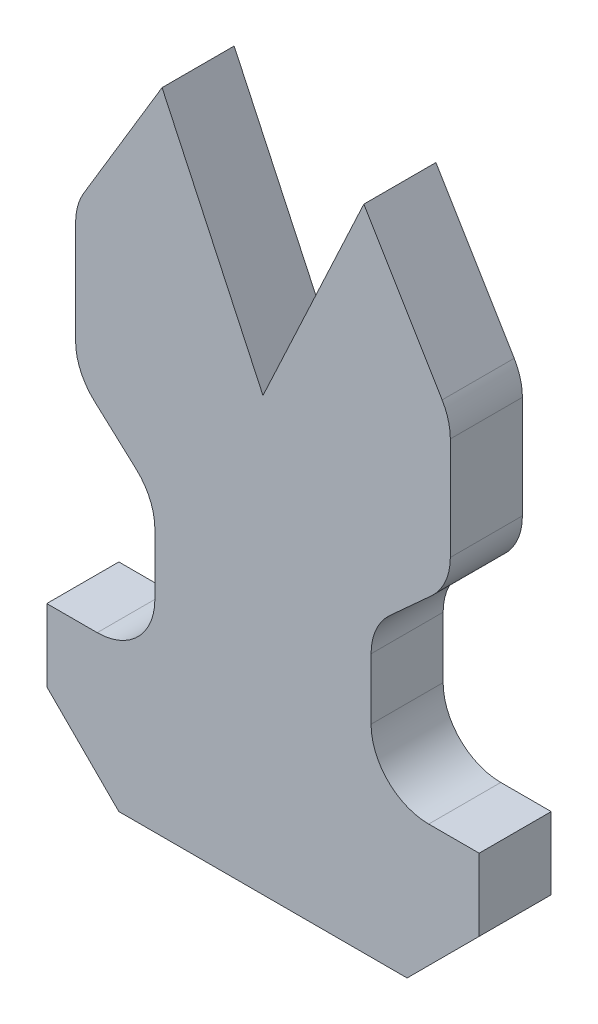
SolidWorks part; units mm, degrees
ref_plane "Piano frontale" through (0, 0, 0) normal (0, 0, 1) x (1, 0, 0)
ref_plane "Piano superiore" through (0, 0, 0) normal (0, 1, 0) x (1, 0, 0)
ref_plane "Piano destro" through (0, 0, 0) normal (1, 0, 0) x (0, 0, -1)
sketch "Schizzo1" plane through (0, 0, 0) normal (0, 0, 1) x (1, 0, 0)
  line L0 (0, 2.0281) -> (0, -3) construction
  line L1 (-1, -3) -> (1, -3)
  line L2 (1.5, -2.5) -> (1.5, -2)
  line L3 (1.5, -2) -> (1.15, -2)
  line L4 (0.75, -1.6) -> (0.75, -1.1769)
  line L5 (0.8809, -0.881) -> (1.1691, -0.619)
  line L6 (1.3, -0.3231) -> (1.3, 0.3892)
  line L7 (1.243, 0.595) -> (0.7, 1.5)
  line L8 (0.7, 1.5) -> (0, 0)
  line L9 (1, -3) -> (1.5, -2.5)
  line L10 (-1, -3) -> (-1.5, -2.5)
  line L11 (-0.7, 1.5) -> (0, 0)
  line L12 (-1.243, 0.595) -> (-0.7, 1.5)
  line L13 (-1.3, -0.3231) -> (-1.3, 0.3892)
  line L14 (-0.8809, -0.881) -> (-1.1691, -0.619)
  line L15 (-0.75, -1.6) -> (-0.75, -1.1769)
  line L16 (-1.5, -2) -> (-1.15, -2)
  line L17 (-1.5, -2.5) -> (-1.5, -2)
  arc A0 (1.15, -2) -> (0.75, -1.6) centre (1.15, -1.6) cw
  arc A1 (0.75, -1.1769) -> (0.8809, -0.881) centre (1.15, -1.1769) cw
  arc A2 (1.1691, -0.619) -> (1.3, -0.3231) centre (0.9, -0.3231) ccw
  arc A3 (1.3, 0.3892) -> (1.243, 0.595) centre (0.9, 0.3892) ccw
  arc A4 (-1.3, 0.3892) -> (-1.243, 0.595) centre (-0.9, 0.3892) cw
  arc A5 (-1.1691, -0.619) -> (-1.3, -0.3231) centre (-0.9, -0.3231) cw
  arc A6 (-0.75, -1.1769) -> (-0.8809, -0.881) centre (-1.15, -1.1769) ccw
  arc A7 (-1.15, -2) -> (-0.75, -1.6) centre (-1.15, -1.6) ccw
  point P3 (1.5, -3)
  point P13 (0.75, -2)
  point P16 (0.75, -1)
  point P19 (1.3, -0.5)
  point P22 (1.3, 0.5)
  point P41 (-1.3, 0.5)
  point P42 (-1.3, -0.5)
  point P43 (-0.75, -1)
  point P44 (-0.75, -2)
  point P45 (-1.5, -3)
  dimension "D11" = 0.4
  dimension "D1" = 4.5
  dimension "D2" = 1.5
  dimension "D3" = 0.75
  dimension "D4" = 1
  dimension "D5" = 1.5
  dimension "D6" = 0.7
  dimension "D7" = 1.3
  dimension "D8" = 1
  dimension "D9" = 0.5
  dimension "D10" = 1
extrude "Estrusione-Estrusione1" add sketch "Schizzo1" along normal blind 0.5
